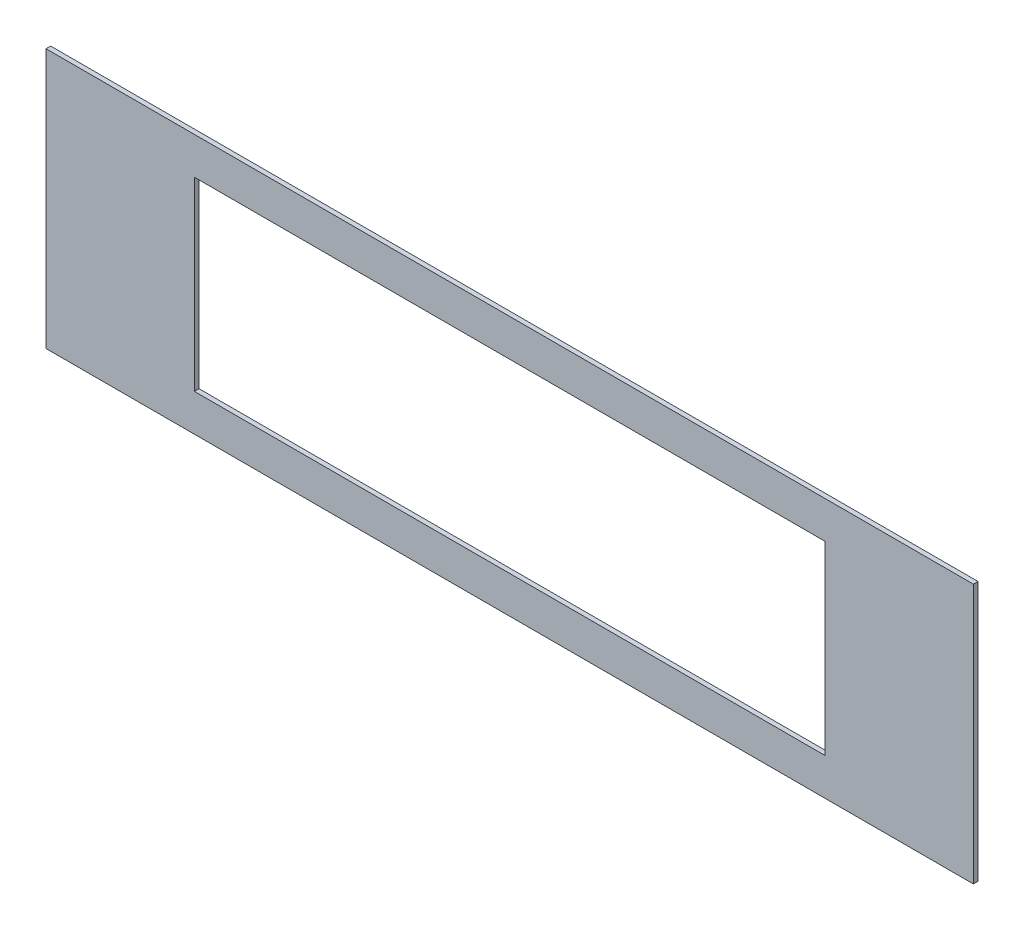
SolidWorks part; units mm, degrees
material "Pine"
ref_plane "Front Plane" through (0, 0, 0) normal (0, 0, 1) x (1, 0, 0)
ref_plane "Top Plane" through (0, 0, 0) normal (0, 1, 0) x (1, 0, 0)
ref_plane "Right Plane" through (0, 0, 0) normal (1, 0, 0) x (0, 0, -1)
sketch "Sketch1" plane through (0, 0, 0) normal (0, 0, 1) x (1, 0, 0)
  line L1 (431.8, -127) -> (-431.8, -127)
  line L2 (431.8, -127) -> (431.8, 127)
  line L3 (431.8, 127) -> (-431.8, 127)
  line L4 (-431.8, -127) -> (-431.8, 127)
  line L5 (431.8, -127) -> (-431.8, 127) construction
  line L6 (431.8, 127) -> (-431.8, -127) construction
  line L7 (635, -177.8) -> (-635, -177.8)
  line L8 (635, -177.8) -> (635, 177.8)
  line L9 (635, 177.8) -> (-635, 177.8)
  line L10 (-635, -177.8) -> (-635, 177.8)
  line L11 (635, -177.8) -> (-635, 177.8) construction
  line L12 (635, 177.8) -> (-635, -177.8) construction
  point P0 (0, 0)
  point P6 (0, 0)
  dimension "D1" = 863.6
  dimension "D2" = 254
  dimension "D3" = 50.8
  dimension "D4" = 1270
extrude "Boss-Extrude1" add sketch "Sketch1" along normal blind 6.35
